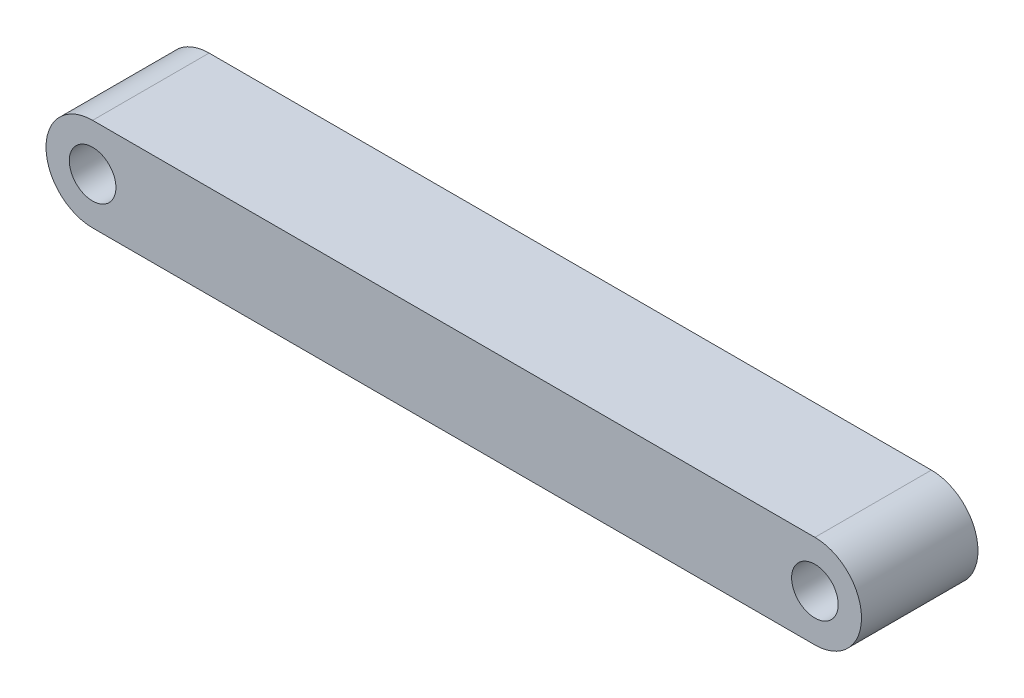
SolidWorks part; units mm, degrees
ref_plane "Alzado" through (0, 0, 0) normal (0, 0, 1) x (1, 0, 0)
ref_plane "Planta" through (0, 0, 0) normal (0, 1, 0) x (1, 0, 0)
ref_plane "Vista lateral" through (0, 0, 0) normal (1, 0, 0) x (0, 0, -1)
sketch "Croquis1" plane through (0, 0, 0) normal (0, 0, 1) x (1, 0, 0)
  line L0 (0, 4) -> (62, 4)
  line L1 (0, 0) -> (62, 0) construction
  line L2 (0, -4) -> (62, -4)
  arc A0 (0, 4) -> (0, -4) centre (0, 0) ccw
  circle A1 centre (0, 0) radius 2
  arc A2 (62, -4) -> (62, 4) centre (62, 0) ccw
  circle A3 centre (62, 0) radius 2
  dimension "D1" = 8
  dimension "D2" = 4
  dimension "D3" = 4
  dimension "D4" = 62
extrude "Saliente-Extruir1" add sketch "Croquis1" along normal blind 10
